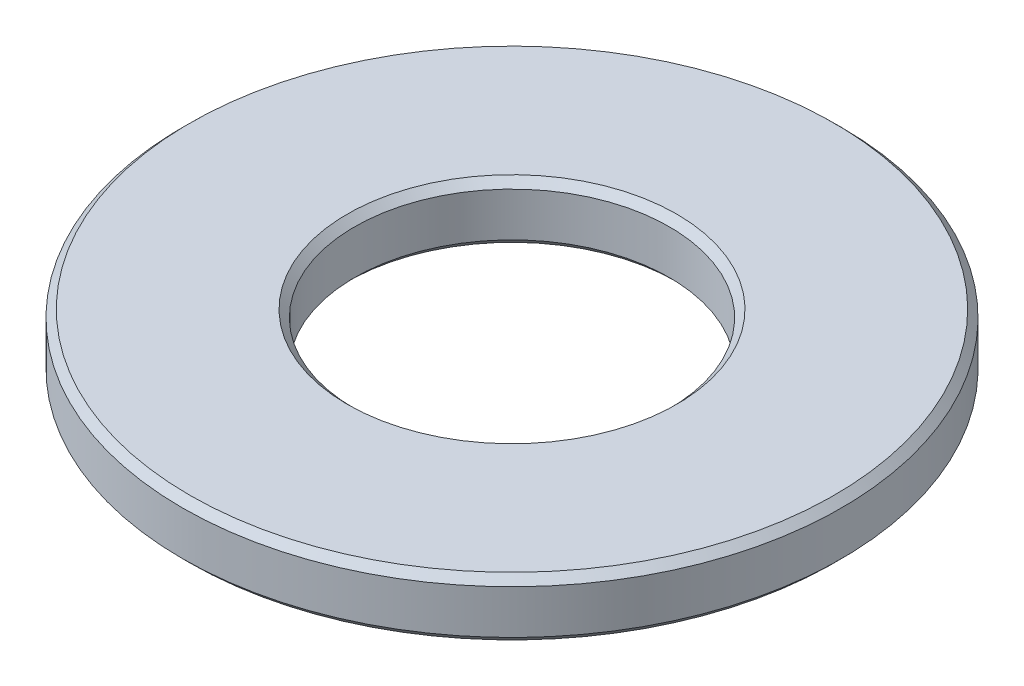
SolidWorks part; units mm, degrees
ref_plane "Front Plane" through (0, 0, 0) normal (0, 0, 1) x (1, 0, 0)
ref_plane "Top Plane" through (0, 0, 0) normal (0, 1, 0) x (1, 0, 0)
ref_plane "Right Plane" through (0, 0, 0) normal (1, 0, 0) x (0, 0, -1)
sketch "Sketch1" plane through (0, 0, 0) normal (0, 1, 0) x (1, 0, 0)
  circle A0 centre (0, 0) radius 2.15
  circle A1 centre (0, 0) radius 4.5
  dimension "D1" = 4.3
  dimension "D2" = 9
extrude "Boss-Extrude1" add sketch "Sketch1" along normal blind 0.8
chamfer "Chamfer1" distance 0.1 angle 45 4 edges at (0, 0, 2.15) (0, 0, 4.5) (0, 0.8, 4.5) (0, 0.8, 2.15)
